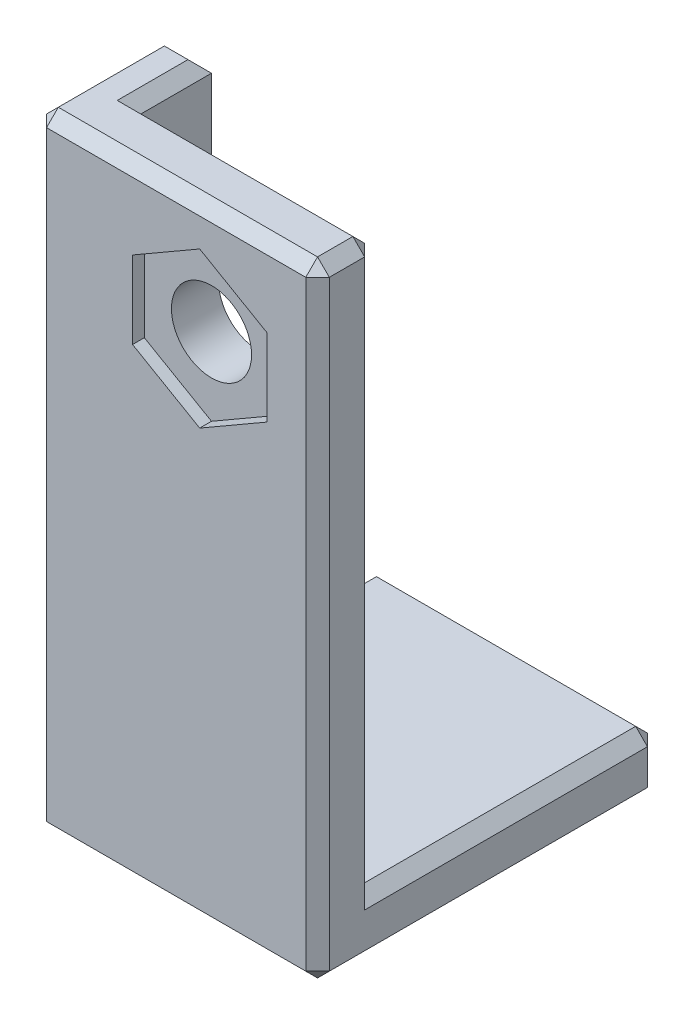
SolidWorks part; units mm, degrees
ref_plane "Front Plane" through (0, 0, 0) normal (0, 0, 1) x (1, 0, 0)
ref_plane "Top Plane" through (0, 0, 0) normal (0, 1, 0) x (1, 0, 0)
ref_plane "Right Plane" through (0, 0, 0) normal (1, 0, 0) x (0, 0, -1)
sketch "Sketch1" plane through (0, 0, 0) normal (1, 0, 0) x (0, 0, -1)
  line L1 (0, 0) -> (2.5, 0)
  line L2 (0, 0) -> (0, 26.5)
  line L3 (0, 26.5) -> (2.5, 26.5)
  line L4 (2.5, 0) -> (2.5, 26.5)
  line L5 (0, 0) -> (14.5, 0)
  line L6 (0, 0) -> (0, 2.5)
  line L7 (0, 2.5) -> (14.5, 2.5)
  line L8 (14.5, 0) -> (14.5, 2.5)
  dimension "D1" = 2.5
  dimension "D2" = 26.5
  dimension "D3" = 12
  dimension "D4" = 2.5
extrude "Boss-Extrude1" add sketch "Sketch1" along normal blind 10 contours L2 L7 L4 L3 | L5 L8 L7 L4 | L7 L2 L1 L4
sketch "Sketch2" plane through (0, 0, 0) normal (0, 0, 1) x (1, 0, 0)
  line L0 (5, 26.5) -> (5, 19.8) construction
  line L1 (10, 26.5) -> (0, 26.5) construction
  circle A0 centre (5, 21.5) radius 1.7
  dimension "D2" = 3.4
  dimension "D1" = 5
extrude "Cut-Extrude1" cut sketch "Sketch2" against normal blind 10 contours L0 A0 | A0 L0
sketch "Sketch4" plane through (0, 0, 0) normal (0, 0, 1) x (1, 0, 0)
  line L0 (0, 0) -> (0, 26.5) construction
  line L1 (5, 24.7909) -> (2.15, 23.1454)
  line L2 (2.15, 23.1454) -> (2.15, 19.8546)
  line L3 (2.15, 19.8546) -> (5, 18.2091)
  line L4 (5, 18.2091) -> (7.85, 19.8546)
  line L5 (7.85, 19.8546) -> (7.85, 23.1454)
  line L6 (7.85, 23.1454) -> (5, 24.7909)
  circle A0 centre (5, 21.5) radius 2.85 construction
  dimension "D1" = 5.7
extrude "Cut-Extrude2" cut sketch "Sketch4" against normal blind 0.5
sketch "Sketch5" plane through (0, 0, 0) normal (-1, 0, 0) x (0, 0, 1)
  line L1 (0, 0) -> (-5.5, 0)
  line L2 (0, 0) -> (0, 26.5)
  line L3 (0, 26.5) -> (-5.5, 26.5)
  line L4 (-5.5, 0) -> (-5.5, 26.5)
  line L5 (-14.5, 2.5) -> (-5.5, 2.5)
  line L6 (-14.5, 2.5) -> (-14.5, 0)
  line L7 (-14.5, 0) -> (-5.5, 0)
  line L8 (-5.5, 2.5) -> (-5.5, 0)
  line M5 (0, 0) -> (0, 26.5)
  line M6 (0, 26.5) -> (-2.5, 26.5)
  line M7 (-2.5, 26.5) -> (-2.5, 2.5)
  line M8 (-2.5, 2.5) -> (-14.5, 2.5)
  line M9 (-14.5, 2.5) -> (-14.5, 0)
  line M10 (-14.5, 0) -> (0, 0)
  dimension "D1" = 5.5
extrude "Boss-Extrude2" add sketch "Sketch5" along normal blind 2 contours L4 L3 M8 M7 | L4 M10 M5 M6 M7 M8 | L4 M10 M8 M9
chamfer "Chamfer1" distance 0.5 angle 45 19 edges at (-1, 26.5, -5.5) (0, 26.5, -4) (5, 26.5, -2.5) (10, 14.5, -2.5) (10, 2.5, -8.5) (-2, 14.5, -5.5) (-2, 2.5, -10) (4, 2.5, -14.5) (-2, 1.25, -14.5) (10, 1.25, -14.5) (4, 0, 0) (-2, 13.25, 0) (10, 13.25, 0) (-2, 0, -7.25) (10, 0, -7.25) (4, 0, -14.5) (4, 26.5, 0) (-2, 26.5, -2.75) (10, 26.5, -1.25)
